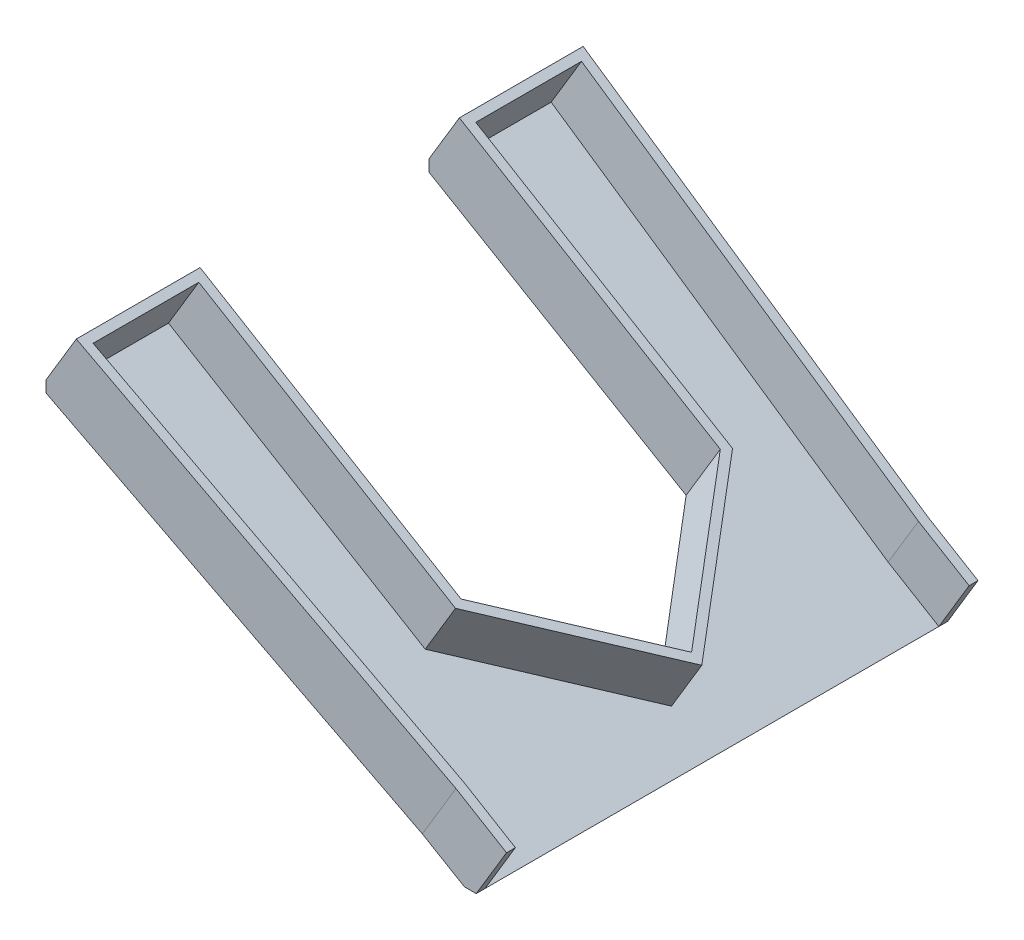
SolidWorks part; units mm, degrees
ref_plane "Спереди" through (0, 0, 0) normal (0, 0, 1) x (1, 0, 0)
ref_plane "Сверху" through (0, 0, 0) normal (0, 1, 0) x (1, 0, 0)
ref_plane "Справа" through (0, 0, 0) normal (1, 0, 0) x (0, 0, -1)
sketch "Эскиз1" plane through (0, 0, 0) normal (0, 0, 1) x (1, 0, 0)
  line L0 (-35, 38) -> (35, -4)
  line L2 (35, -4) -> (35, 38)
  line L3 (35, 38) -> (-35, 38) construction
  line L4 (-35, 36) -> (-35, 38)
  line L5 (35, -38) -> (-35, 38) construction
  line L6 (35, 38) -> (-35, -38) construction
  line L7 (-35, 36) -> (33, -4)
  line L8 (35, -4) -> (33, -4)
  line L9 (33, -4) -> (-35, 36)
  line L10 (-35, 36) -> (-35, 38)
  line L11 (-35, 38) -> (35, -4)
  point P0 (0, 0)
  point P6 (35, -4)
  point P7 (33, -4)
  point P9 (-35, 36)
  dimension "D1" = 76
  dimension "D2" = 34
  dimension "D3" = 2
  dimension "D4" = 2
  dimension "D5" = 70
extrude "Бобышка-Вытянуть1" add sketch "Эскиз1" along normal blind 86 contours L8 L0 L4 L7
sketch "Эскиз2" plane through (7.5, 12.5, 0) normal (0.5145, 0.8575, 0) x (0.8575, -0.5145, 0)
  line L0 (32.0702, -86) -> (32.0702, 0) construction
  line L1 (-49.5631, -86) -> (22.0702, -83)
  line L2 (22.0702, -83) -> (32.0702, -83)
  line L3 (32.0702, -83) -> (32.0702, -86)
  line L4 (32.0702, -86) -> (-49.5631, -86)
  line L5 (-49.5631, -86) -> (-49.7193, -86.1342)
  line L6 (32.0702, -43) -> (-49.5631, -43) construction
  line L7 (-49.5631, -86) -> (-49.5631, 0) construction
  line L8 (-49.6259, -84.5013) -> (22.0388, -81.5) construction
  line L9 (22.0388, -81.5) -> (32.0702, -81.5) construction
  line L10 (-49.5631, -65) -> (32.0702, -65) construction
  line L11 (-49.5631, -66.5) -> (32.0702, -66.5) construction
  line L12 (2.0702, -65) -> (22.0388, -43)
  line L13 (2.0702, -65) -> (-49.5631, -65)
  line L14 (-49.5631, -43) -> (22.0388, -43)
  line L15 (32.0702, -3) -> (32.0702, 0)
  line L16 (-49.5631, -21) -> (-49.5631, -65)
  line L17 (22.0702, -3) -> (32.0702, -3)
  line L18 (-49.5631, 0) -> (22.0702, -3)
  line L19 (32.0702, 0) -> (-49.5631, 0)
  line L20 (2.0702, -21) -> (-49.5631, -21)
  line L21 (2.0702, -21) -> (22.0388, -43)
  point P0 (32.0702, -43)
  point P1 (32.0702, -86)
  point P4 (32.0702, 0)
  point P6 (32.0702, -83)
  point P8 (22.0702, -83)
  point P23 (32.0702, -65)
  point P24 (-49.5631, -66.5)
  point P28 (2.0702, -65)
  point P29 (22.0388, -43)
  line M14 (32.0702, 0) -> (-49.5631, 0)
  line M15 (-49.5631, 0) -> (-49.5631, -86)
  line M16 (-49.5631, -86) -> (32.0702, -86)
  line M17 (32.0702, -86) -> (32.0702, 0)
  dimension "D1" = 40
  dimension "D2" = 10
  dimension "D5" = 1.5
  dimension "D6" = 30
  dimension "D4" = 21
  dimension "D3" = 1.5
extrude "Вырез-Вытянуть1" cut sketch "Эскиз2" against normal blind 3 contours L18 L17 M14 M17 | L21 L20 L14 M15 | L14 L13 L12 M15 | L2 L1 M16 M17
sketch "Эскиз3" plane through (7.5, 12.5, 0) normal (0.5145, 0.8575, 0) x (0.8575, -0.5145, 0)
  line L0 (-49.5631, -86) -> (-49.5631, -65)
  line L1 (-49.5631, -65) -> (2.0702, -65)
  line L2 (2.0702, -65) -> (22.0388, -43)
  line L3 (22.0388, -43) -> (2.0702, -21)
  line L4 (2.0702, -21) -> (-49.5631, -21)
  line L5 (-49.5631, -21) -> (-49.5631, 0)
  line L6 (-49.5631, 0) -> (22.0702, -3)
  line L7 (22.0702, -3) -> (32.0702, -3)
  line L8 (32.0702, -83) -> (22.0702, -83)
  line L9 (22.0702, -83) -> (-49.5631, -86)
  line L10 (32.0702, -81.5) -> (22.0388, -81.5)
  line L11 (22.0388, -81.5) -> (-48.0631, -84.4359)
  line L12 (-48.0631, -84.4359) -> (-48.0631, -66.5)
  line L13 (-48.0631, -66.5) -> (2.7345, -66.5)
  line L14 (2.7345, -66.5) -> (24.0646, -43)
  line L15 (24.0646, -43) -> (2.7345, -19.5)
  line L16 (2.7345, -19.5) -> (-48.0631, -19.5)
  line L17 (-48.0631, -19.5) -> (-48.0631, -1.5641)
  line L18 (-48.0631, -1.5641) -> (22.0388, -4.5)
  line L19 (22.0388, -4.5) -> (32.0702, -4.5)
  line L20 (32.0702, -81.5) -> (32.0702, -83)
  line L21 (32.0702, -4.5) -> (32.0702, -3)
  line L22 (32.0702, -3) -> (32.0218, -2.9744)
  line M1 (-49.5631, -86) -> (22.0702, -83)
  line M2 (22.0702, -83) -> (32.0702, -83)
  line M3 (32.0702, -83) -> (32.0702, -3)
  line M4 (32.0702, -3) -> (22.0702, -3)
  line M5 (22.0702, -3) -> (-49.5631, 0)
  line M6 (-49.5631, 0) -> (-49.5631, -21)
  line M7 (-49.5631, -21) -> (2.0702, -21)
  line M8 (2.0702, -21) -> (22.0388, -43)
  line M9 (22.0388, -43) -> (2.0702, -65)
  line M10 (2.0702, -65) -> (-49.5631, -65)
  line M11 (-49.5631, -65) -> (-49.5631, -86)
  dimension "D1" = 1.5
extrude "Бобышка-Вытянуть2" add sketch "Эскиз3" along normal blind 10 contours L18 L19 L10 L11 L12 L13 L14 L15 L16 L17 M3 M4 M5 M6 M7 M8 M9 M10 M11 M1 M2
